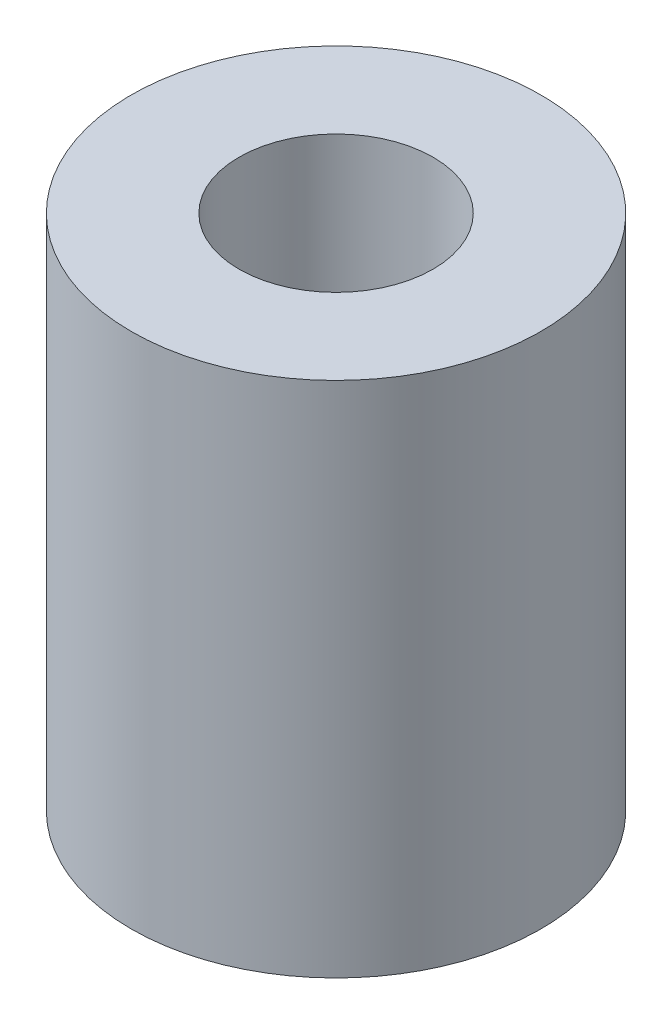
SolidWorks part; units mm, degrees
ref_plane "Front Plane" through (0, 0, 0) normal (0, 0, 1) x (1, 0, 0)
ref_plane "Top Plane" through (0, 0, 0) normal (0, 1, 0) x (1, 0, 0)
ref_plane "Right Plane" through (0, 0, 0) normal (1, 0, 0) x (0, 0, -1)
sketch "Sketch1" plane through (0, 0, 0) normal (0, 1, 0) x (1, 0, 0)
  circle A0 centre (0, 0) radius 9.5
  circle A1 centre (0, 0) radius 3
  dimension "D1" = 19
  dimension "D2" = 6
extrude "Boss-Extrude1" add sketch "Sketch1" along normal blind 8
sketch "Sketch2" plane through (0, 8, 0) normal (0, 1, 0) x (1, 0, 0)
  circle A0 centre (0, 0) radius 9.5
  circle A1 centre (0, 0) radius 4.5
  dimension "D1" = 9
extrude "Boss-Extrude2" add sketch "Sketch2" along normal blind 16
